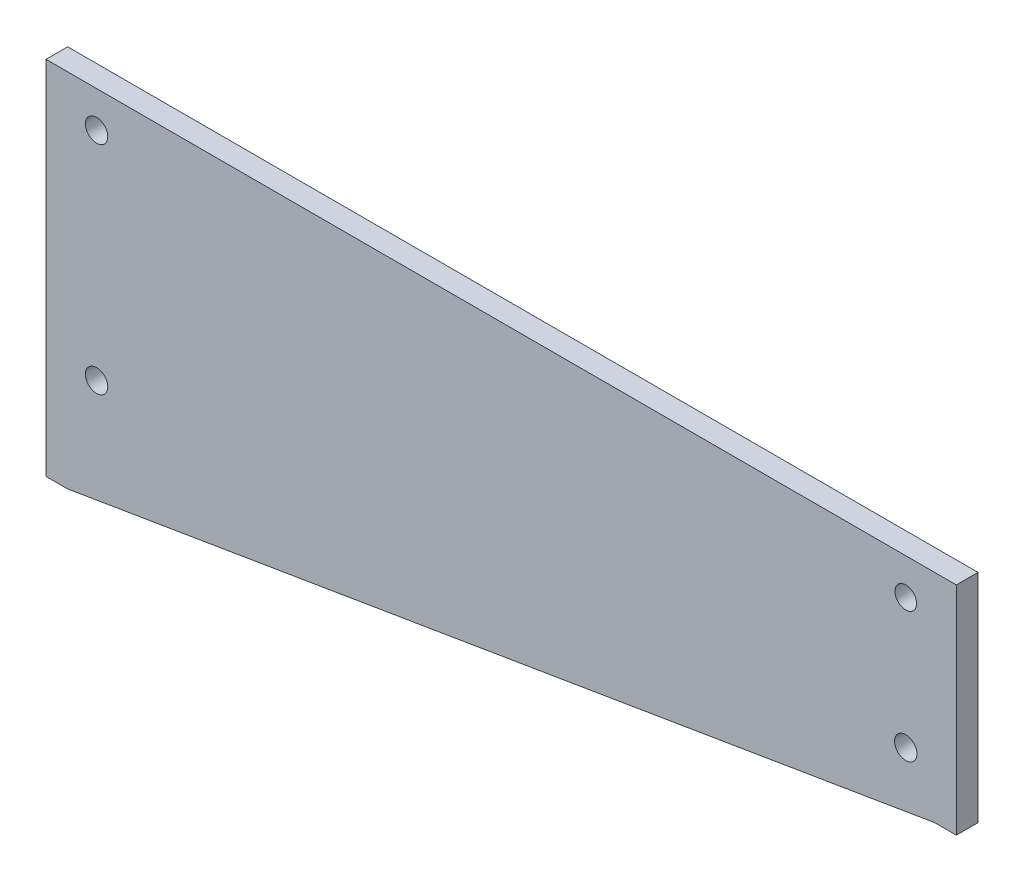
SolidWorks part; units mm, degrees
ref_plane "前视基准面" through (0, 0, 0) normal (0, 0, 1) x (1, 0, 0)
ref_plane "上视基准面" through (0, 0, 0) normal (0, 1, 0) x (1, 0, 0)
ref_plane "右视基准面" through (0, 0, 0) normal (1, 0, 0) x (0, 0, -1)
other "Configuration Table"
sketch "草图1" plane through (0, 0, 0) normal (0, 0, 1) x (1, 0, 0)
  line L1 (63, -26.5) -> (-63, -26.5)
  line L2 (63, -26.5) -> (63, 26.5)
  line L3 (63, 26.5) -> (-63, 26.5)
  line L4 (-63, -26.5) -> (-63, 26.5)
  line L5 (63, -26.5) -> (-63, 26.5) construction
  line L6 (63, 26.5) -> (-63, -26.5) construction
  point P0 (0, 0)
  dimension "D1" = 126
  dimension "D2" = 53
extrude "凸台-拉伸1" add sketch "草图1" along normal blind 3
sketch "草图2" plane through (0, 0, 0) normal (0, 0, -1) x (-1, 0, 0)
  line L0 (-63, 26.5) -> (63, 26.5) construction
  line L1 (-63, -26.5) -> (-63, 26.5) construction
  line L2 (63, 26.5) -> (63, -26.5) construction
  circle A0 centre (56, 21.5) radius 1.55
  circle A1 centre (-56, 21.5) radius 1.5
  dimension "D1" = 5
  dimension "D2" = 5
  dimension "D3" = 7
  dimension "D4" = 7
extrude "切除-拉伸1" cut sketch "草图2" against normal blind 10 contours A0 | A1
sketch "草图3" plane through (0, 0, 3) normal (0, 0, 1) x (1, 0, 0)
  line L0 (-56, 21.5) -> (-56, -8.5) construction
  line L1 (56, 21.5) -> (56, -8.5) construction
  circle A0 centre (-56, -8.5) radius 1.55
  circle A1 centre (56, -8.5) radius 1.55
  dimension "D1" = 3.1
  dimension "D2" = 3.1
  dimension "D3" = 30
extrude "切除-拉伸2" cut sketch "草图3" against normal blind 10
sketch "草图4" plane through (0, 0, 3) normal (0, 0, 1) x (1, 0, 0)
  line L0 (-56, 21.5) -> (-56, 3.5) construction
  line L1 (0, 0) -> (0, -11.8695) construction
  circle A0 centre (-56, 3.5) radius 1.55
  circle A1 centre (56, 3.5) radius 1.55
  dimension "D1" = 3.1
  dimension "D2" = 18
sketch "草图5" plane through (0, 0, 3) normal (0, 0, 1) x (1, 0, 0)
  circle A0 centre (56, 3.5) radius 1.55 construction
  circle A1 centre (56, 3.5) radius 1.55
extrude "切除-拉伸5" cut sketch "草图5" against normal blind 10
sketch "草图6" plane through (0, 0, 3) normal (0, 0, 1) x (1, 0, 0)
  line L0 (62.9804, -3.5) -> (60, -3.5)
  line L1 (60, -3.5) -> (63, -3.5) construction
  line L2 (62.9804, -21.9696) -> (62.9804, 14.9696) construction
  line L3 (60, -3.5) -> (60, 26.5) construction
  line L4 (-60, -23.5) -> (-63, -23.5)
  line L5 (-63, 26.5) -> (-63, -26.5) construction
  line L6 (-63, -23.5) -> (-60, -23.5) construction
  line L7 (-60, -23.5) -> (60, -3.5)
  line L8 (-63, -23.5) -> (-63, -26.5)
  line L9 (-63, -26.5) -> (63, -26.5)
  line L10 (-63, -26.5) -> (63, -26.5) construction
  line L13 (62.9804, -3.5) -> (63, -3.5)
  line L14 (63, -26.5) -> (63, 26.5) construction
  line L15 (63, -3.5) -> (63, -26.5)
extrude "切除-拉伸7" cut sketch "草图6" against normal through all
